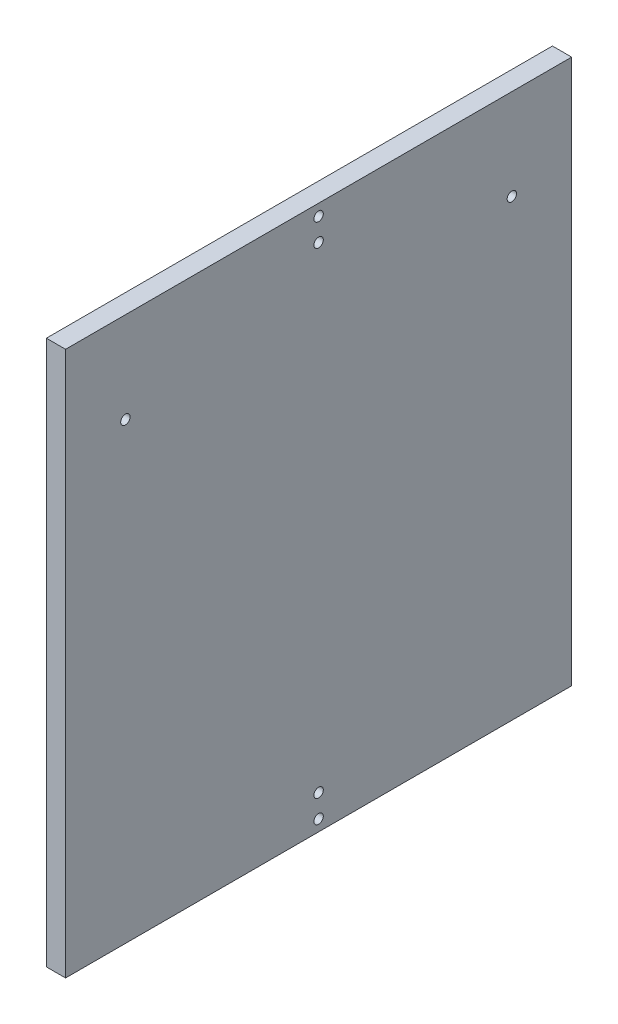
SolidWorks part; units mm, degrees
ref_plane "Front Plane" through (0, 0, 0) normal (0, 0, 1) x (1, 0, 0)
ref_plane "Top Plane" through (0, 0, 0) normal (0, 1, 0) x (1, 0, 0)
ref_plane "Right Plane" through (0, 0, 0) normal (1, 0, 0) x (0, 0, -1)
sketch "Sketch1" plane through (0, 0, 0) normal (1, 0, 0) x (0, 0, -1)
  line L1 (83.65, -90) -> (-83.65, -90)
  line L2 (83.65, -90) -> (83.65, 90)
  line L3 (83.65, 90) -> (-83.65, 90)
  line L4 (-83.65, -90) -> (-83.65, 90)
  line L5 (83.65, -90) -> (-83.65, 90) construction
  line L6 (83.65, 90) -> (-83.65, -90) construction
  point P0 (0, 0)
  dimension "D1" = 167.3
  dimension "D2" = 180
extrude "Boss-Extrude1" add sketch "Sketch1" along normal blind 6.35
sketch "Sketch2" plane through (0, 0, 0) normal (-1, 0, 0) x (0, 0, 1)
  line L0 (-63.883, 60) -> (63.883, 60) construction
  line L1 (-83.65, 90) -> (83.65, 90) construction
  circle A0 centre (-63.883, 60) radius 1.55
  circle A1 centre (63.883, 60) radius 1.55
  point P2 (0, 60)
  point P3 (0, 90)
  dimension "D1" = 3.1
  dimension "D2" = 127.7661
  dimension "D3" = 30
extrude "Cut-Extrude1" cut sketch "Sketch2" against normal through all
hole_wizard "Ø3.0mm Clearance Dowel Hole1" positions "Sketch5" profile "Sketch4" hole size "Ø3.0" standard "DIN" end condition through all
sketch "Sketch5" plane through (0, 0, 0) normal (-1, 0, 0) x (0, 0, 1)
  line L0 (0, 90) -> (0, -90) construction
  line L1 (-83.65, 90) -> (83.65, 90) construction
  line L2 (83.65, -90) -> (-83.65, -90) construction
  line L3 (-83.65, 0) -> (83.65, 0) construction
  line L4 (-83.65, -90) -> (-83.65, 90) construction
  line L5 (83.65, 90) -> (83.65, -90) construction
  point P11 (0, 86.25)
  point P13 (0, 78.75)
  point P28 (0, -78.75)
  point P29 (0, -86.25)
other "AlignGroup1" parameters "D1"=0, "D2"=3.75, "D3"=11.25
sketch "Sketch4" plane through (0, 86.25, 0) normal (0, 1, 0) x (0, 0, 1)
  line L0 (0, 0) -> (0, 6.35)
  line L1 (0, 6.35) -> (1.554, 6.35)
  line L2 (1.554, 6.35) -> (1.554, 0)
  line L5 (1.554, 0) -> (0, 0)
  line L11 (0, -6.35) -> (0, 107.95) construction
  dimension "Thru Hole Dia." = 3.108
  dimension "Thru Hole Depth" = 6.35
